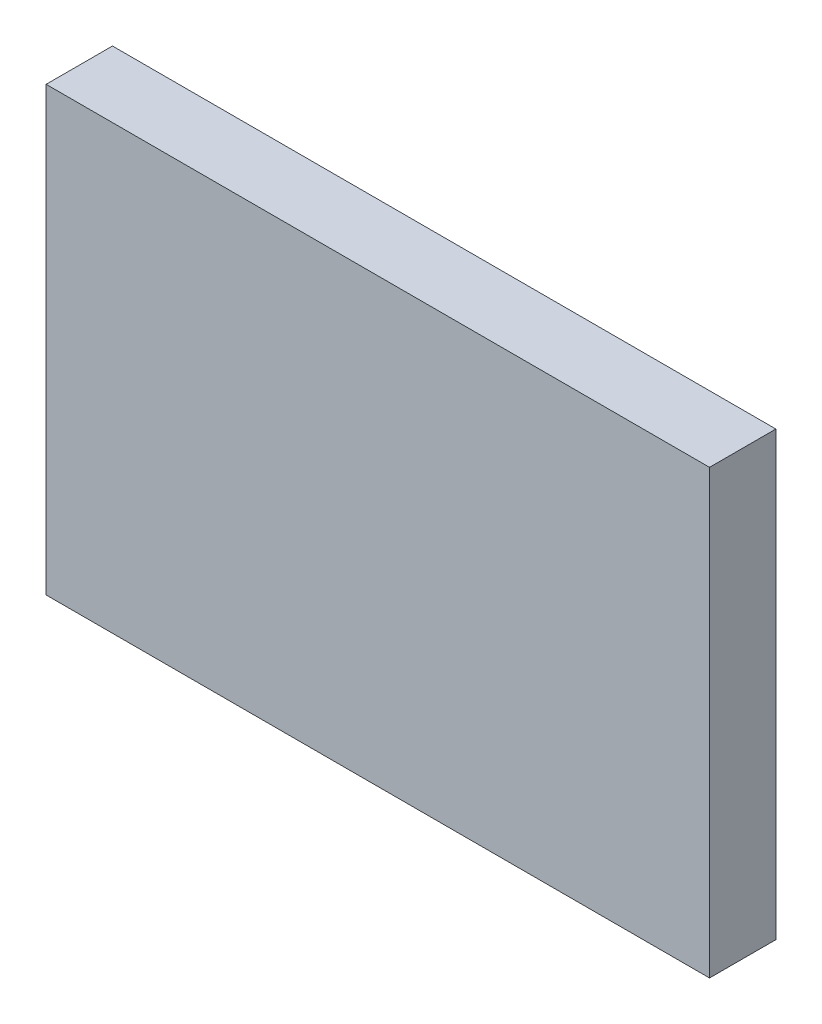
SolidWorks part; units mm, degrees
ref_plane "Front Plane" through (0, 0, 0) normal (0, 0, 1) x (1, 0, 0)
ref_plane "Top Plane" through (0, 0, 0) normal (0, 1, 0) x (1, 0, 0)
ref_plane "Right Plane" through (0, 0, 0) normal (1, 0, 0) x (0, 0, -1)
sketch "Sketch1" plane through (0, 0, 0) normal (0, 0, 1) x (1, 0, 0)
  line L1 (0, 0) -> (60, 0)
  line L2 (0, 0) -> (0, 40)
  line L3 (0, 40) -> (60, 40)
  line L4 (60, 0) -> (60, 40)
  dimension "D1" = 40
  dimension "D2" = 60
extrude "Boss-Extrude1" add sketch "Sketch1" along normal blind 6
